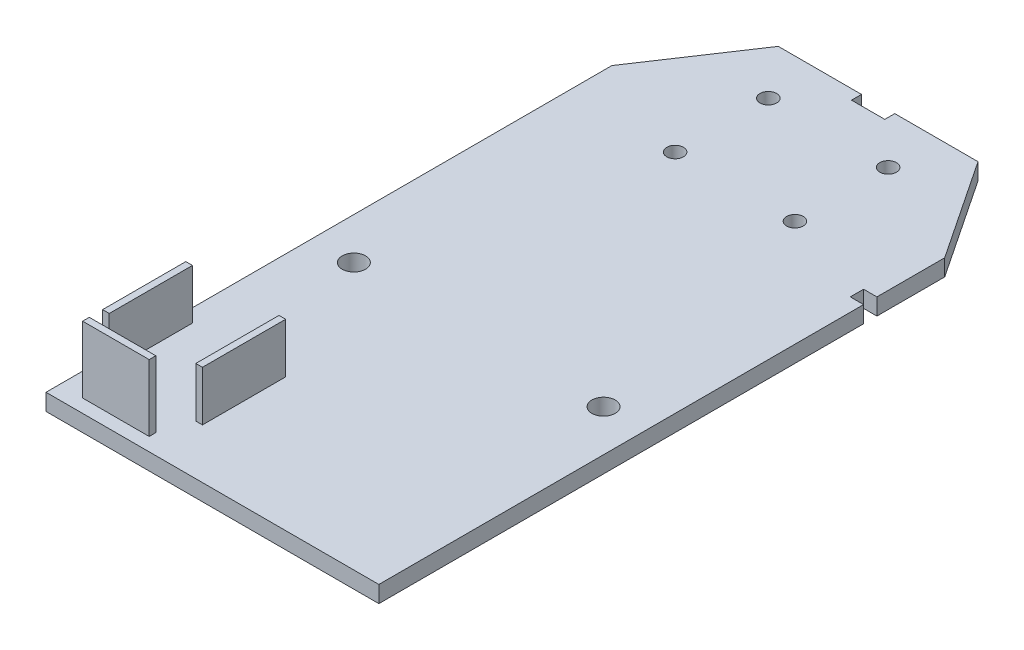
SolidWorks part; units mm, degrees
ref_plane "Alzado" through (0, 0, 0) normal (0, 0, 1) x (1, 0, 0)
ref_plane "Planta" through (0, 0, 0) normal (0, 1, 0) x (1, 0, 0)
ref_plane "Vista lateral" through (0, 0, 0) normal (1, 0, 0) x (0, 0, -1)
sketch "Croquis1" plane through (0, 0, 0) normal (0, 1, 0) x (1, 0, 0)
  line L0 (50, 0) -> (50, 200) construction
  line L1 (0, 0) -> (100, 0)
  line L2 (0, 0) -> (0, 200)
  line L3 (0, 200) -> (100, 200)
  line L4 (100, 0) -> (100, 200)
  line L5 (12, 1.9965) -> (12, 0)
  line L6 (12, 1.9965) -> (2, 1.9965)
  line L7 (2, 1.9965) -> (2, 16.9965)
  line L8 (2, 16.9965) -> (0, 16.9965)
  line L9 (88, 1.9965) -> (88, 0)
  line L10 (88, 1.9965) -> (98, 1.9965)
  line L11 (98, 16.9965) -> (100, 16.9965)
  line L12 (98, 1.9965) -> (98, 16.9965)
  dimension "D1" = 200
  dimension "D2" = 100
  dimension "D3" = 10
  dimension "D4" = 2
  dimension "D5" = 1.9965
  dimension "D6" = 15
extrude "Saliente-Extruir3" add sketch "Croquis1" along normal blind 5 contours L2 L1 L4 L3
sketch "Croquis2" plane through (0, 0, 0) normal (0, -1, 0) x (1, 0, 0)
  line L0 (50, 0) -> (50, -200) construction
  line L1 (0, 0) -> (100, 0) construction
  line L2 (0, -200) -> (100, -200) construction
  line L3 (0, -17) -> (2, -17)
  line L4 (0, 0) -> (0, -200) construction
  line L5 (2, -17) -> (2, -2)
  line L6 (2, -2) -> (12, -2)
  line L7 (12, -2) -> (12, 0)
  line L8 (88, -2) -> (88, 0)
  line L9 (98, -2) -> (88, -2)
  line L10 (100, -17) -> (98, -17)
  line L11 (98, -17) -> (98, -2)
  line L12 (0, -17) -> (0, 0)
  line L13 (0, 0) -> (12, 0)
  dimension "D1" = 10
  dimension "D2" = 15
  dimension "D3" = 2
  dimension "D4" = 2
sketch "Croquis3" plane through (0, 0, 0) normal (0, -1, 0) x (1, 0, 0)
  line L0 (100, 0) -> (88, 0)
  line L1 (100, -17) -> (98, -17)
  line L2 (100, 0) -> (100, -200) construction
  line L3 (98, -17) -> (98, -2)
  line L4 (98, -2) -> (88, -2)
  line L5 (88, -2) -> (88, 0)
  line L10 (0, 0) -> (100, 0) construction
  line L12 (100, -17) -> (100, 0)
  dimension "D1" = 2
  dimension "D2" = 10
  dimension "D3" = 2
  dimension "D4" = 15
sketch "Croquis5" plane through (0, 5, 0) normal (0, 1, 0) x (1, 0, 0)
  line L0 (50, 200) -> (50, 0) construction
  line L1 (0, 200) -> (100, 200) construction
  line L2 (0, 0) -> (100, 0) construction
  line L3 (32, 185) -> (68, 185) construction
  line L4 (0, 0) -> (0, 200) construction
  line L6 (32, 157) -> (68, 157) construction
  circle A0 centre (32, 185) radius 2.5
  circle A1 centre (68, 185) radius 2.5
  circle A2 centre (32, 157) radius 2.5
  circle A3 centre (68, 157) radius 2.5
  dimension "D5" = 5
  dimension "D6" = 5
  dimension "D7" = 5
  dimension "D8" = 5
  dimension "D1" = 36
  dimension "D2" = 32
  dimension "D3" = 15
  dimension "D4" = 28
sketch "Croquis7" plane through (0, 5, 0) normal (0, 1, 0) x (1, 0, 0)
extrude "Cortar-Extruir1" cut sketch "Croquis5" against normal through all
sketch "Croquis9" plane through (0, 5, 0) normal (0, 1, 0) x (1, 0, 0)
sketch "Croquis11" plane through (0, 5, 0) normal (0, 1, 0) x (1, 0, 0)
  line L0 (50, 0) -> (50, 80) construction
  line L1 (0, 0) -> (100, 0) construction
  line L2 (12.5, 80) -> (87.5, 80) construction
  line L3 (0, 0) -> (0, 200) construction
  circle A0 centre (12.5, 80) radius 3.5
  circle A1 centre (87.5, 80) radius 3.5
  dimension "D4" = 7
  dimension "D5" = 7
  dimension "D1" = 80
  dimension "D2" = 75
  dimension "D3" = 12.5
extrude "Cortar-Extruir5" cut sketch "Croquis11" against normal through all
sketch "Croquis12" plane through (0, 5, 0) normal (0, 1, 0) x (1, 0, 0)
  line L0 (50, 200) -> (50, 183.469) construction
  line L1 (0, 200) -> (100, 200) construction
  line L3 (45, 200) -> (45, 197)
  line L4 (55, 200) -> (55, 197)
  line L5 (45, 197) -> (55, 197)
  line L6 (45, 200) -> (55, 200)
  dimension "D1" = 3
  dimension "D2" = 5
extrude "Cortar-Extruir6" cut sketch "Croquis12" against normal through all contours L6 L4 L5 L3
sketch "Croquis13" plane through (0, 5, 0) normal (0, 1, 0) x (1, 0, 0)
  line L0 (20, 200) -> (20, 195) construction
  line L1 (0, 200) -> (45, 200) construction
  line L2 (0, 0) -> (0, 200) construction
  line L3 (0, 170) -> (5, 170) construction
  line L4 (80, 200) -> (80, 195) construction
  line L5 (55, 200) -> (100, 200) construction
  line L6 (100, 0) -> (100, 200) construction
  line L7 (100, 170) -> (95, 170) construction
  line L8 (0, 170) -> (20, 200)
  line L9 (20, 200) -> (0, 200)
  line L10 (0, 200) -> (0, 170)
  line L11 (100, 170) -> (80, 200)
  line L12 (80, 200) -> (100, 200)
  line L13 (100, 200) -> (100, 170)
  dimension "D1" = 5
  dimension "D2" = 20
  dimension "D3" = 5
  dimension "D4" = 30
  dimension "D5" = 5
  dimension "D6" = 20
  dimension "D7" = 5
  dimension "D8" = 30
extrude "Cortar-Extruir7" cut sketch "Croquis13" against normal through all
sketch "Croquis15" plane through (0, 5, 0) normal (0, 1, 0) x (1, 0, 0)
  line L0 (100, 149.6271) -> (96, 149.6271)
  line L1 (100, 0) -> (100, 170) construction
  line L2 (96, 149.6271) -> (96, 145.6271)
  line L3 (96, 145.6271) -> (100, 145.6271)
  line L4 (100, 149.6271) -> (100, 145.6271)
  dimension "D1" = 4
  dimension "D2" = 4
extrude "Cortar-Extruir9" cut sketch "Croquis15" against normal through all
sketch "Croquis16" plane through (0, 5, 0) normal (0, 1, 0) x (1, 0, 0)
  line L0 (7, 4) -> (27, 4)
  line L1 (27, 4) -> (27, 6)
  line L2 (27, 6) -> (7, 6)
  line L3 (7, 6) -> (7, 4)
  line L4 (0, 0) -> (100, 0) construction
  line L5 (0, 0) -> (0, 170) construction
  dimension "D1" = 2
  dimension "D2" = 20
  dimension "D3" = 4
  dimension "D4" = 7
extrude "Saliente-Extruir6" add sketch "Croquis16" along normal blind 20 separate body
sketch "Croquis17" plane through (0, 5, 0) normal (0, 1, 0) x (1, 0, 0)
  line L0 (17, 6) -> (17, 21.9819) construction
  line L1 (27, 6) -> (7, 6) construction
  line L2 (17, 15) -> (30, 15) construction
  line L4 (0, 0) -> (100, 0) construction
  line L5 (30, 15) -> (30, 40)
  line L6 (30, 40) -> (32, 40)
  line L7 (32, 40) -> (32, 15)
  line L8 (32, 15) -> (30, 15)
  line L9 (4, 40) -> (2, 40)
  line L10 (2, 40) -> (2, 15)
  line L11 (4, 15) -> (4, 40)
  line L12 (2, 15) -> (4, 15)
  dimension "D1" = 13
  dimension "D2" = 15
  dimension "D3" = 2
  dimension "D4" = 25
extrude "Saliente-Extruir7" add sketch "Croquis17" along normal blind 15
